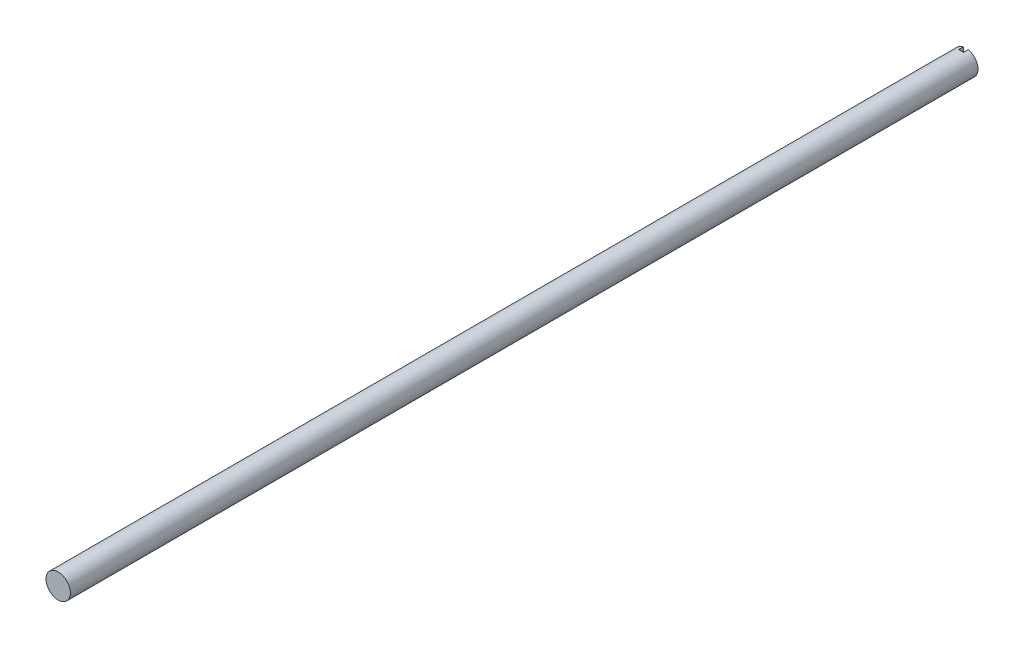
SolidWorks part; units mm, degrees
ref_plane "Plan de face" through (0, 0, 0) normal (0, 0, 1) x (1, 0, 0)
ref_plane "Plan de dessus" through (0, 0, 0) normal (0, 1, 0) x (1, 0, 0)
ref_plane "Plan de droite" through (0, 0, 0) normal (1, 0, 0) x (0, 0, -1)
sketch "Esquisse1" plane through (0, 0, 0) normal (0, 0, 1) x (1, 0, 0)
  circle A0 centre (0, 0) radius 2.5
  dimension "D1" = 5
extrude "Boss.-Extru.1" add sketch "Esquisse1" along normal blind 186
sketch "Esquisse2" plane through (0, 0, 0) normal (0, 0, -1) x (-1, 0, 0)
  line L0 (0, 2.5) -> (0, -2.5) construction
  line L1 (-0.5, 2.4495) -> (-0.5, -2.4495)
  line L2 (0.5, 2.4495) -> (0.5, -2.4495)
  circle A0 centre (0, 0) radius 2.5 construction
  arc A1 (0.5, 2.4495) -> (-0.5, 2.4495) centre (0, 0) ccw
  circle A2 centre (0, 0) radius 2.5
  arc A3 (-0.5, -2.4495) -> (0.5, -2.4495) centre (0, 0) ccw
  point P7 (0, 0)
  dimension "D1" = 0.5
  dimension "D2" = 0
extrude "Enlèv. mat.-Extru.1" cut sketch "Esquisse2" against normal blind 1
